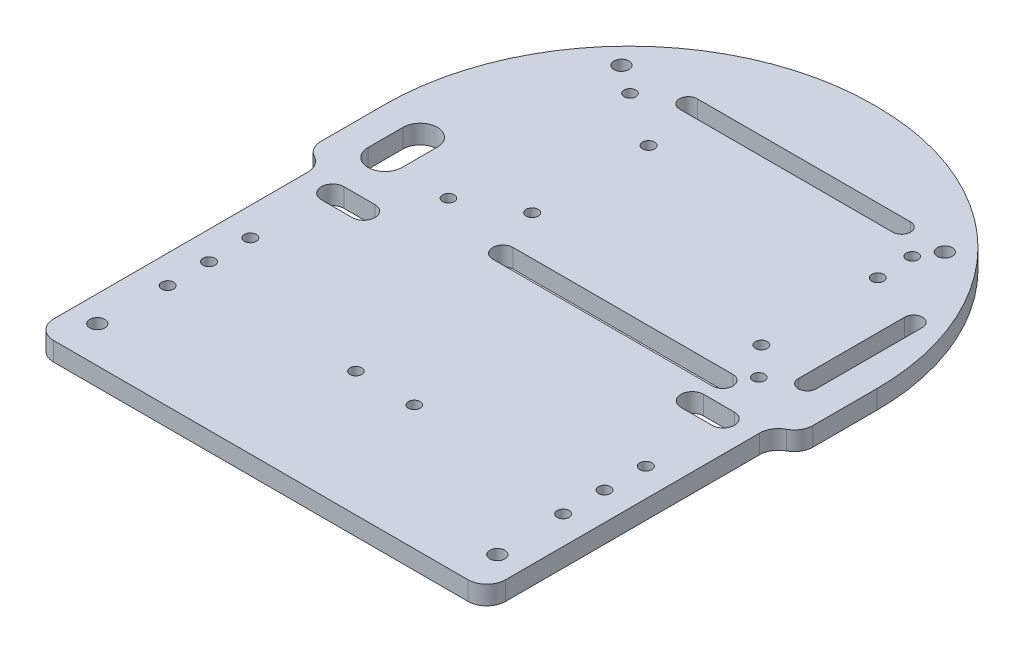
SolidWorks part; units mm, degrees
ref_plane "Front Plane" through (0, 0, 0) normal (0, 0, 1) x (1, 0, 0)
ref_plane "Top Plane" through (0, 0, 0) normal (0, 1, 0) x (1, 0, 0)
ref_plane "Right Plane" through (0, 0, 0) normal (1, 0, 0) x (0, 0, -1)
sketch "Sketch1" plane through (0, 0, 0) normal (0, 1, 0) x (1, 0, 0)
  line L0 (0, 90.99) -> (0, -94.01) construction
  line L1 (-94.5795, 0) -> (90.4205, 0) construction
  line L2 (-65.5, 80) -> (-65.5, -83.5)
  line L3 (-65.5, -83.5) -> (65.5, -83.5)
  line L4 (65.5, -83.5) -> (65.5, 80)
  line L5 (65.5, 80) -> (-65.5, 80)
  line L6 (-65.5, -7) -> (-65.5, -83.5)
  line L7 (-65.5, -83.5) -> (-60.15, -83.5)
  line L8 (-60.15, -83.5) -> (-60.15, -7)
  line L9 (-60.15, -7) -> (-65.5, -7)
  line L10 (60.15, -83.5) -> (60.15, -7)
  line L11 (65.5, -83.5) -> (60.15, -83.5)
  line L12 (65.5, -7) -> (65.5, -83.5)
  line L13 (60.15, -7) -> (65.5, -7)
  dimension "D1" = 60.15
  dimension "D2" = 65.5
  dimension "D3" = 80
  dimension "D4" = 185
  dimension "D5" = 185
  dimension "D7" = 76.5
  dimension "D8" = 87
  dimension "D9" = 65.5
extrude "Boss-Extrude2" add sketch "Sketch1" along normal blind 5 contours L10 L13 L4 L5 L2 L9 L8 L7 L3 L11
fillet "Fillet8" radius 65 2 edges at (65.5, 2.5, -80) (-65.5, 2.5, -80)
sketch "Sketch4" plane through (0, 5, 0) normal (0, 1, 0) x (1, 0, 0)
  line L0 (0, 0) -> (0, 80) construction
  line L1 (0, 80) -> (0, -83.5) construction
  line L2 (-60.15, -83.5) -> (60.15, -83.5) construction
  line L3 (-65.5, 4) -> (65.5, 4) construction
  line L4 (-65.5, 15) -> (-65.5, -7) construction
  line L5 (65.5, -7) -> (65.5, 15) construction
  line L6 (-60.15, -83.5) -> (-60.15, -7) construction
  line L7 (0.5, 80) -> (-0.5, 80) construction
  line L8 (-60.15, -83.5) -> (60.15, -83.5) construction
  line L9 (60.15, -83.5) -> (60.15, -7) construction
  line L10 (-60.15, -45.25) -> (60.15, -45.25) construction
  line L29 (-25.2292, 55.5443) -> (31.548, 55.5443) construction
  line L32 (-60.15, -83.5) -> (-60.15, -7) construction
  line L33 (-60.15, -83.5) -> (60.15, -83.5) construction
  line L34 (-25.2292, 57.9144) -> (31.548, 57.9144)
  line L35 (-25.2292, 53.1741) -> (31.548, 53.1741)
  line L36 (-15.4719, -3.5901) -> (43.0471, -3.5901) construction
  line L37 (-15.4719, -0.8869) -> (43.0471, -0.8869)
  line L38 (-15.4719, -6.2934) -> (43.0471, -6.2934)
  line L39 (55.1066, 35.1494) -> (55.1066, 6.8682) construction
  line L40 (57.4842, 35.1494) -> (57.4842, 6.8682)
  line L41 (52.729, 35.1494) -> (52.729, 6.8682)
  line L42 (-60.15, -83.5) -> (60.15, -83.5) construction
  line L43 (60.15, -83.5) -> (60.15, -7) construction
  line L44 (-65.5, 15) -> (-65.5, -7) construction
  line L45 (-51.9956, -12.3973) -> (-43.7542, -12.3973) construction
  line L46 (-51.9956, -9.3872) -> (-43.7542, -9.3872)
  line L47 (-51.9956, -15.4074) -> (-43.7542, -15.4074)
  line L48 (51.9956, -12.3973) -> (43.7542, -12.3973) construction
  line L49 (51.9956, -9.3872) -> (43.7542, -9.3872)
  line L50 (51.9956, -15.4074) -> (43.7542, -15.4074)
  line L51 (-53.249, 12.1712) -> (-53.249, 2.8053) construction
  line L52 (-48.6846, 12.1712) -> (-48.6846, 2.8053)
  line L53 (-57.8135, 12.1712) -> (-57.8135, 2.8053)
  line L54 (60.15, -83.5) -> (60.15, -7) construction
  circle A38 centre (43.0471, 55.5443) radius 2
  circle A41 centre (-43.0471, 55.5443) radius 2
  circle A51 centre (-53.249, -73.7963) radius 2
  circle A52 centre (53.249, -73.7963) radius 2
  circle A53 centre (-35.419, 50.1936) radius 1.5621
  circle A54 centre (39.7142, 50.1936) radius 1.5621
  circle A55 centre (-35.419, 1.8574) radius 1.5621
  circle A56 centre (47.2072, 1.8574) radius 1.5621
  arc A63 (-25.2292, 57.9144) -> (-25.2292, 53.1741) centre (-25.2292, 55.5443) ccw
  arc A64 (31.548, 53.1741) -> (31.548, 57.9144) centre (31.548, 55.5443) ccw
  arc A65 (-15.4719, -0.8869) -> (-15.4719, -6.2934) centre (-15.4719, -3.5901) ccw
  arc A66 (43.0471, -6.2934) -> (43.0471, -0.8869) centre (43.0471, -3.5901) ccw
  arc A67 (57.4842, 35.1494) -> (52.729, 35.1494) centre (55.1066, 35.1494) ccw
  arc A68 (52.729, 6.8682) -> (57.4842, 6.8682) centre (55.1066, 6.8682) ccw
  circle A69 centre (-7.869, -50.3336) radius 1.5558
  circle A70 centre (7.6885, -50.3336) radius 1.5558
  arc A71 (-51.9956, -9.3872) -> (-51.9956, -15.4074) centre (-51.9956, -12.3973) ccw
  arc A72 (-43.7542, -15.4074) -> (-43.7542, -9.3872) centre (-43.7542, -12.3973) ccw
  arc A73 (51.9956, -9.3872) -> (51.9956, -15.4074) centre (51.9956, -12.3973) cw
  arc A74 (43.7542, -15.4074) -> (43.7542, -9.3872) centre (43.7542, -12.3973) cw
  circle A75 centre (40.0716, 40.6621) radius 1.6
  circle A76 centre (40.0716, 9.6621) radius 1.6
  circle A77 centre (-20.9284, 40.6621) radius 1.6
  circle A78 centre (-20.9284, 9.6621) radius 1.6
  arc A79 (-48.6846, 12.1712) -> (-57.8135, 12.1712) centre (-53.249, 12.1712) ccw
  arc A80 (-57.8135, 2.8053) -> (-48.6846, 2.8053) centre (-53.249, 2.8053) ccw
  circle A81 centre (52.65, -33.6599) radius 1.6
  circle A82 centre (52.65, -44.6599) radius 1.6
  circle A83 centre (52.65, -55.6599) radius 1.6
  circle A84 centre (-52.65, -55.6599) radius 1.6
  circle A85 centre (-52.65, -44.6599) radius 1.6
  circle A86 centre (-52.65, -33.6599) radius 1.6
  point P26 (0, 40)
  point P27 (-53.249, 7.4883)
  point P39 (3.1594, 55.5443)
  point P50 (55.1066, 21.0088)
  point P54 (13.7876, -3.5901)
  point P70 (-47.8749, -12.3973)
  point P87 (47.8749, -12.3973)
  point P104 (0, 0)
  point P105 (0, 0)
  point P106 (52.7184, -40.0592)
  point P107 (0, 0)
  dimension "D2" = 3.1242
  dimension "D13" = 4
  dimension "D10" = 124.1621
  dimension "D11" = 31
  dimension "D5" = 3.1242
  dimension "D6" = 2.7033
  dimension "D7" = 58.519
  dimension "D18" = 39.7142
  dimension "D8" = 3.2
  dimension "D22" = 15.4719
  dimension "D23" = 55.1066
  dimension "D3" = 3.1242
  dimension "D4" = 3.1242
  dimension "D9" = 20.9284
  dimension "D12" = 20.9284
  dimension "D20" = 47.2072
  dimension "D21" = 4
  dimension "D24" = 2.3776
  dimension "D26" = 79.9099
  dimension "D25" = 28.2812
  dimension "D37" = 2.3702
  dimension "D38" = 28.602
  dimension "D45" = 3.1115
  dimension "D46" = 3.1115
  dimension "D51" = 3.0101
  dimension "D32" = 4.5645
  dimension "D35" = 3.2
  dimension "D14" = 6.901
  dimension "D15" = 9.7037
  dimension "D16" = 40.0716
  dimension "D17" = 35.419
  dimension "D19" = 35.419
  dimension "D27" = 85.3574
  dimension "D28" = 85.3574
  dimension "D29" = 31
  dimension "D30" = 93.1621
  dimension "D31" = 124.1621
  dimension "D33" = 9.366
  dimension "D34" = 86.3053
  dimension "D36" = 7.5
  dimension "D39" = 40.2708
  dimension "D40" = 90.3682
  dimension "D41" = 49.8401
  dimension "D42" = 11
  dimension "D43" = 133.6936
  dimension "D44" = 133.6936
  dimension "D47" = 7.869
  dimension "D48" = 7.6885
  dimension "D49" = 33.1664
  dimension "D50" = 33.1664
  dimension "D52" = 43.7542
  dimension "D53" = 8.2414
  dimension "D54" = 71.1027
  dimension "D55" = 11
  dimension "D56" = 7.5
  dimension "D57" = 7.5
extrude "Cut-Extrude1" cut sketch "Sketch4" against normal blind 5
ref_plane "Plane1" through (60.15, 5, 7) normal (0, 0, -1) x (-1, 0, 0)
fillet "Fillet9" radius 5 4 edges at (65.5, 2.5, 7) (60.15, 2.5, 83.5) (-60.15, 2.5, 83.5) (-65.5, 2.5, 7)
fillet "Fillet10" radius 5 2 edges at (60.15, 2.5, 7) (-60.15, 2.5, 7)
